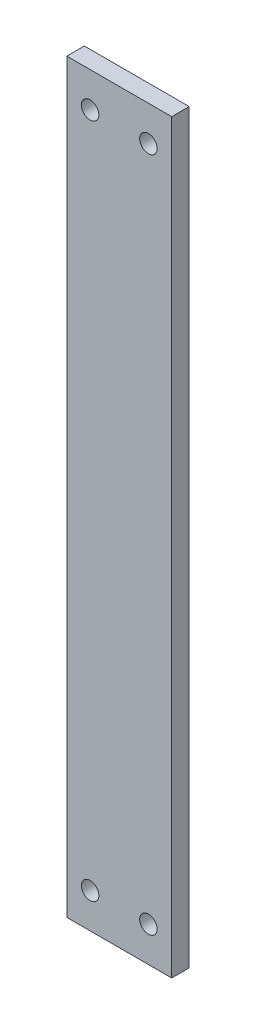
SolidWorks part; units mm, degrees
ref_plane "Front Plane" through (0, 0, 0) normal (0, 0, 1) x (1, 0, 0)
ref_plane "Top Plane" through (0, 0, 0) normal (0, 1, 0) x (1, 0, 0)
ref_plane "Right Plane" through (0, 0, 0) normal (1, 0, 0) x (0, 0, -1)
sketch "Sketch1" plane through (0, 0, 0) normal (0, 0, 1) x (1, 0, 0)
  line L0 (9, 6) -> (9, 0) construction
  line L1 (0, 0) -> (18, 0)
  line L2 (0, 0) -> (0, 128)
  line L3 (0, 128) -> (18, 128)
  line L4 (18, 0) -> (18, 128)
  line L5 (4, 6) -> (14, 6) construction
  line L6 (9, 6) -> (9, 122) construction
  line L7 (4, 122) -> (14, 122) construction
  line L8 (4, 122) -> (4, 6) construction
  circle A0 centre (4, 6) radius 1.5
  circle A1 centre (14, 6) radius 1.5
  circle A2 centre (4, 122) radius 1.5
  circle A3 centre (14, 122) radius 1.5
  dimension "D6" = 3
  dimension "D2" = 18
  dimension "D5" = 10
  dimension "D3" = 6
  dimension "D4" = 116
  dimension "D1" = 6
extrude "Boss-Extrude1" add sketch "Sketch1" along normal blind 3
equation "\"Height\"= \"Trolley Profile@Plasma Beta.Assembly\" + 16"
equation "\"D4@Sketch1\"=\"Height\""
